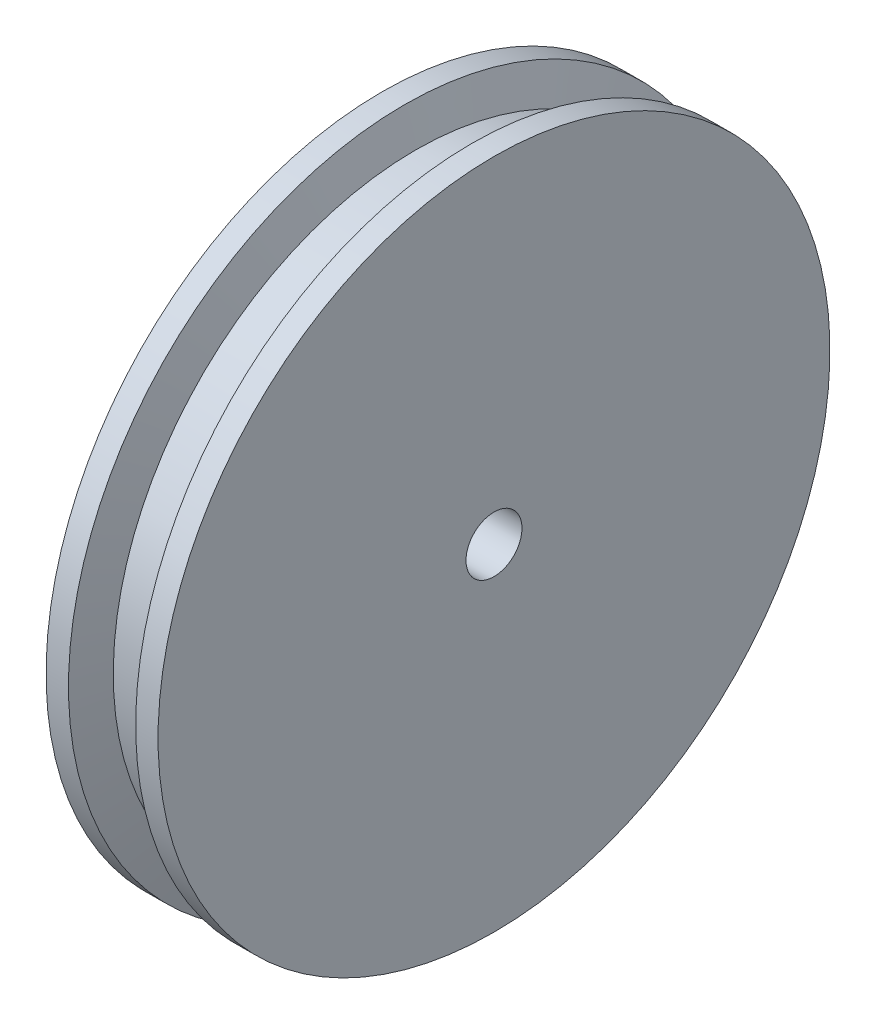
SolidWorks part; units mm, degrees
ref_plane "Front Plane" through (0, 0, 0) normal (0, 0, 1) x (1, 0, 0)
ref_plane "Top Plane" through (0, 0, 0) normal (0, 1, 0) x (1, 0, 0)
ref_plane "Right Plane" through (0, 0, 0) normal (1, 0, 0) x (0, 0, -1)
sketch "Sketch3" plane through (0, 0, 0) normal (0, 0, 1) x (1, 0, 0)
  line L0 (0, 0) -> (0, 30)
  line L1 (0, 30) -> (2, 30)
  line L2 (2, 30) -> (3, 27)
  line L3 (3, 27) -> (7, 27)
  line L4 (7, 27) -> (8, 30)
  line L5 (8, 30) -> (10, 30)
  line L6 (10, 30) -> (10, 0)
  line L7 (10, 0) -> (0, 0)
  dimension "D1" = 30
  dimension "D2" = 2
  dimension "D3" = 2
  dimension "D4" = 10
  dimension "D5" = 4
  dimension "D6" = 3
  dimension "D7" = 30
  dimension "D8" = 1
revolve "Revolve1" add sketch "Sketch3" angle 360 about L7
sketch "Sketch4" plane through (10, 0, 0) normal (1, 0, 0) x (0, 0, -1)
  circle A0 centre (0, 0) radius 2.5
  dimension "D1" = 5
extrude "Cut-Extrude2" cut sketch "Sketch4" against normal blind 10
